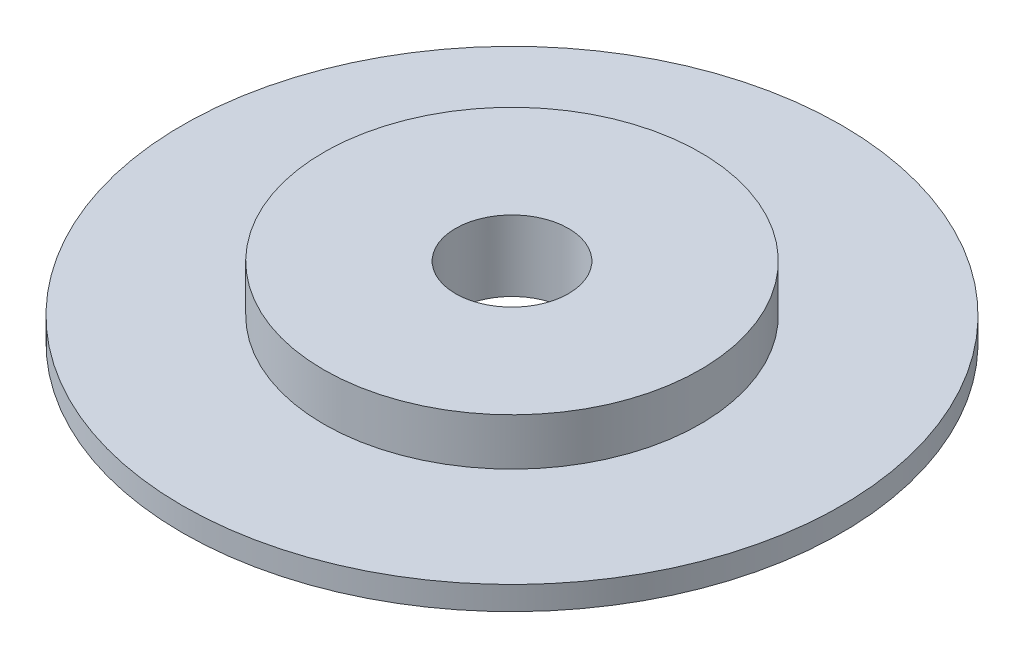
SolidWorks part; units mm, degrees
ref_plane "Front Plane" through (0, 0, 0) normal (0, 0, 1) x (1, 0, 0)
ref_plane "Top Plane" through (0, 0, 0) normal (0, 1, 0) x (1, 0, 0)
ref_plane "Right Plane" through (0, 0, 0) normal (1, 0, 0) x (0, 0, -1)
sketch "Sketch1" plane through (0, 0, 0) normal (0, 1, 0) x (1, 0, 0)
  circle A0 centre (0, 0) radius 7
  dimension "D1" = 14
extrude "Boss-Extrude1" add sketch "Sketch1" along normal blind 1.5
sketch "Sketch2" plane through (0, 1.5, 0) normal (0, 1, 0) x (1, 0, 0)
  circle A0 centre (0, 0) radius 4
  circle A1 centre (0, 0) radius 7
  dimension "D1" = 8
extrude "Cut-Extrude1" cut sketch "Sketch2" against normal blind 1
hole_wizard "M2 Clearance Hole1" positions "Sketch3" profile "Sketch4" hole size "M2" standard "ISO"
sketch "Sketch3" plane through (0, 0, 0) normal (0, -1, 0) x (-1, 0, 0)
  point P0 (0, 0)
sketch "Sketch4" plane through (0, 0, 0) normal (1, 0, 0) x (0, 0, -1)
  line L0 (0, 0) -> (0, 3.721)
  line L1 (0, 3.721) -> (1.2, 3)
  line L2 (1.2, 3) -> (1.2, 0)
  line L5 (1.2, 0) -> (0, 0)
  line L10 (0, 3.721) -> (-1.2, 3) construction
  line L11 (0, -6.35) -> (0, 107.95) construction
  dimension "Hole Dia." = 2.4
  dimension "Hole Depth" = 3
  dimension "Drill Angle" = 118
